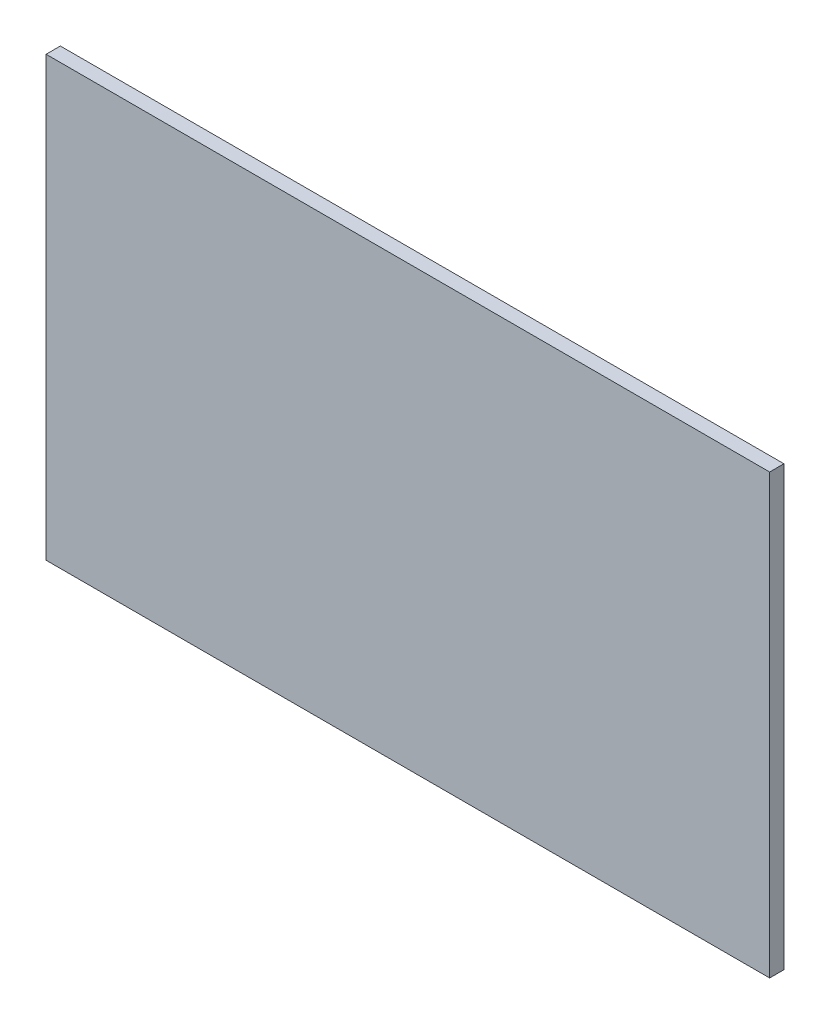
SolidWorks part; units mm, degrees
ref_plane "前视基准面" through (0, 0, 0) normal (0, 0, 1) x (1, 0, 0)
ref_plane "上视基准面" through (0, 0, 0) normal (0, 1, 0) x (1, 0, 0)
ref_plane "右视基准面" through (0, 0, 0) normal (1, 0, 0) x (0, 0, -1)
sketch "草图1" plane through (0, 0, 0) normal (0, 0, 1) x (1, 0, 0)
  line L0 (0, 0) -> (355, 0)
  line L1 (355, 0) -> (355, -215)
  line L2 (355, -215) -> (0, -215)
  line L5 (0, 0) -> (0, -215)
  dimension "D1" = 355
  dimension "D2" = 215
extrude "凸台-拉伸1" add sketch "草图1" along normal blind 7
sketch "草图2" plane through (0, 0, 0) normal (0, 0, -1) x (-1, 0, 0)
  line L0 (-177.5, 0) -> (-177.5, -215) construction
  line L1 (-355, 0) -> (0, 0) construction
  line L2 (0, -215) -> (-355, -215) construction
  line L3 (-177.5, -215) -> (-177.5, -175) construction
  line L4 (-177.5, -175) -> (-107.5, -175)
  line L5 (-107.5, -175) -> (-107.5, -125)
  line L6 (-107.5, -125) -> (-107.5, -105)
  line L7 (-107.5, -105) -> (-247.5, -105)
  line L8 (-247.5, -105) -> (-247.5, -175)
  line L9 (-247.5, -175) -> (-177.5, -175)
  line L10 (-177.5, -135) -> (-192.5, -135) construction
  line L11 (-355, 0) -> (0, 0) construction
  line L12 (-177.5, -175) -> (-177.5, -145) construction
  line L13 (-177.5, -175) -> (-177.5, -135) construction
  circle A0 centre (-177.5, -135) radius 3
  circle A1 centre (-192.5, -135) radius 0.5
  point P16 (-177.5, -135.6296)
  dimension "D6" = 6
  dimension "D8" = 1
  dimension "D1" = 40
  dimension "D2" = 70
  dimension "D3" = 50
  dimension "D4" = 20
  dimension "D5" = 140
  dimension "D7" = 15
  dimension "D9" = 40
extrude "凸台-拉伸2" add sketch "草图2" along normal blind 7
